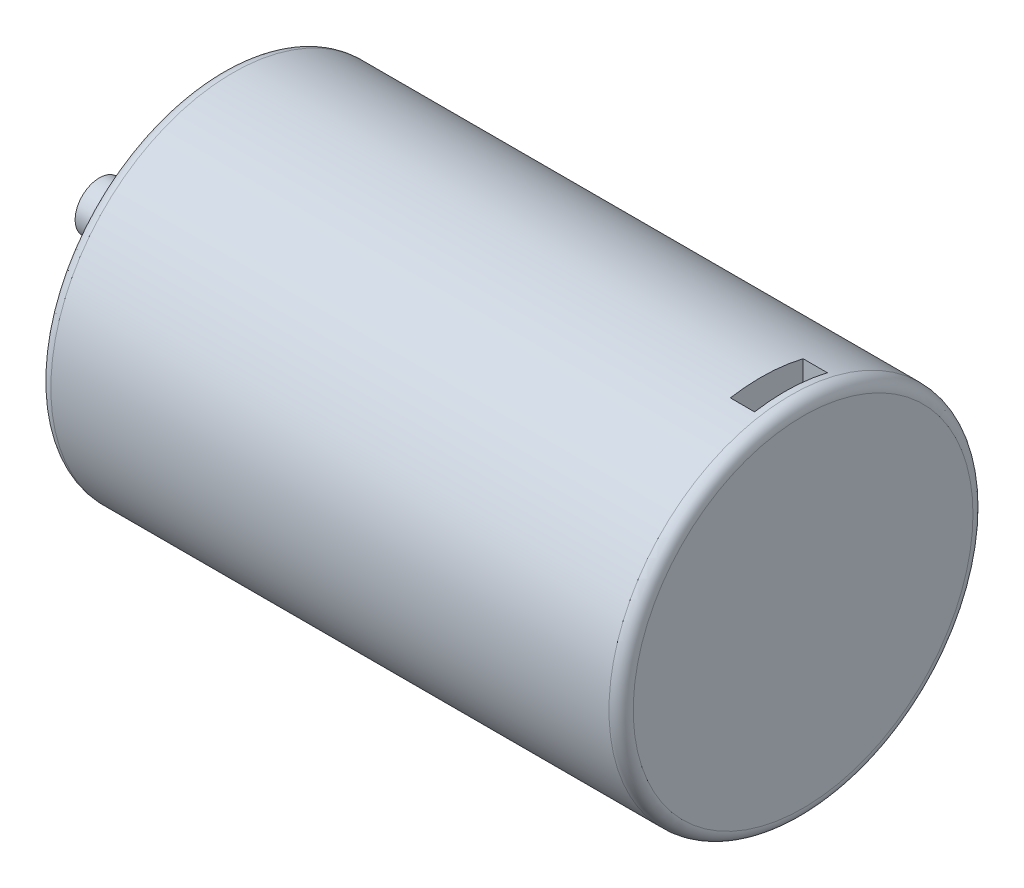
SolidWorks part; units mm, degrees
ref_plane "前视基准面" through (0, 0, 0) normal (0, 0, 1) x (1, 0, 0)
ref_plane "上视基准面" through (0, 0, 0) normal (0, 1, 0) x (1, 0, 0)
ref_plane "右视基准面" through (0, 0, 0) normal (1, 0, 0) x (0, 0, -1)
sketch "草图1" plane through (0, 0, 0) normal (1, 0, 0) x (0, 0, -1)
  circle A0 centre (0, 0) radius 15
extrude "凸台-拉伸1" add sketch "草图1" against normal blind 48
sketch "草图2" plane through (-48, 0, 0) normal (-1, 0, 0) x (0, 0, 1)
  circle A0 centre (0, 0) radius 2
extrude "凸台-拉伸2" add sketch "草图2" along normal blind 10
sketch "草图3" plane through (-48, 0, 0) normal (-1, 0, 0) x (0, 0, 1)
  circle A0 centre (0, 0) radius 3
extrude "凸台-拉伸3" add sketch "草图3" along normal blind 3
fillet "圆角1" radius 1 1 edges at (-48, 0, -15)
fillet "圆角2" radius 1 1 edges at (0, 0, -15)
sketch "草图4" plane through (0, 0, 0) normal (0, 1, 0) x (1, 0, 0)
  line L0 (-61.0858, 0) -> (0.9946, 0) construction
  line L2 (-3.5, 3.5) -> (-1.5, 3.5)
  line L3 (-3.5, 3.5) -> (-3.5, -2.5)
  line L4 (-3.5, -2.5) -> (-1.5, -2.5)
  line L5 (-1.5, 3.5) -> (-1.5, -2.5)
  point P7 (0, 0)
  point P8 (0, 0)
  point P9 (0, 0)
  point P10 (0, 0)
  point P11 (0, 0)
extrude "切除-拉伸1" cut sketch "草图4" against normal blind 3 from offset 15
